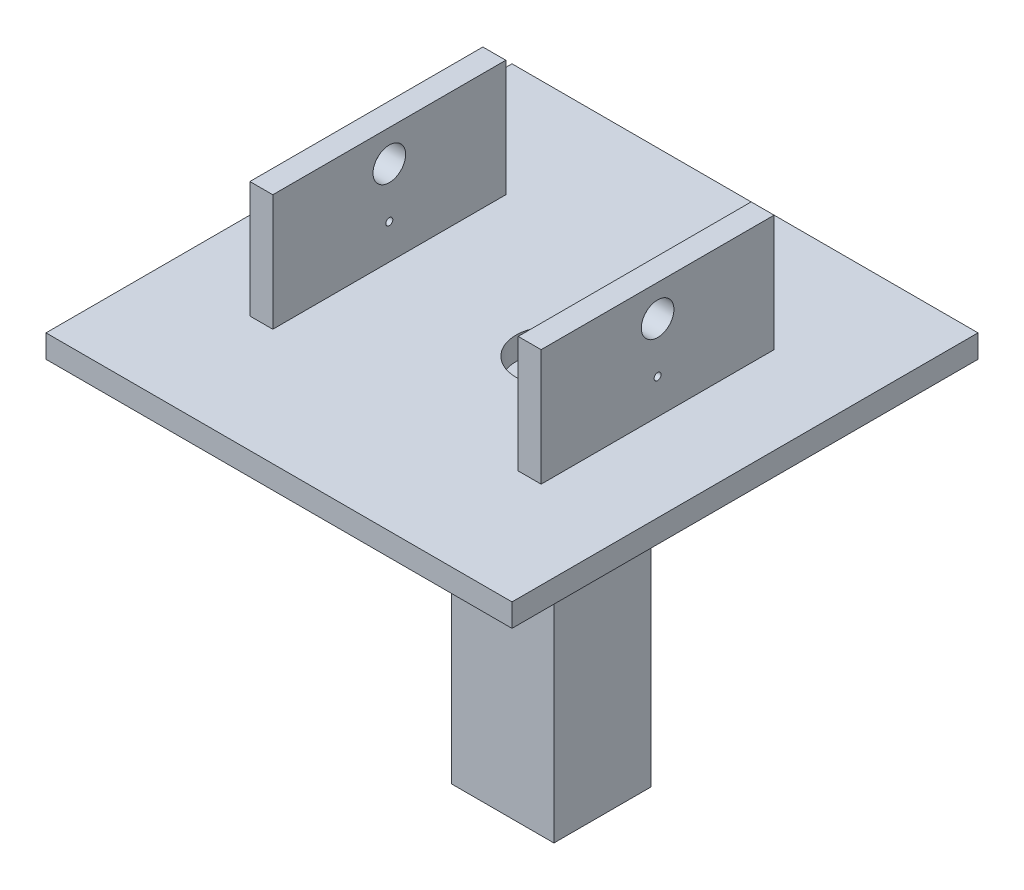
SolidWorks part; units mm, degrees
ref_plane "Front Plane" through (0, 0, 0) normal (0, 0, 1) x (1, 0, 0)
ref_plane "Top Plane" through (0, 0, 0) normal (0, 1, 0) x (1, 0, 0)
ref_plane "Right Plane" through (0, 0, 0) normal (1, 0, 0) x (0, 0, -1)
sketch "Sketch2" plane through (0, 0, 0) normal (0, 1, 0) x (1, 0, 0)
  line L1 (0, 0) -> (101.6, 0)
  line L2 (0, 0) -> (0, -101.6)
  line L3 (0, -101.6) -> (101.6, -101.6)
  line L4 (101.6, 0) -> (101.6, -101.6)
  dimension "D1" = 101.6
  dimension "D2" = 101.6
extrude "Boss-Extrude2" add sketch "Sketch2" along normal blind 5
sketch "Sketch3" plane through (0, 5, 0) normal (0, 1, 0) x (1, 0, 0)
  line L0 (0, 0) -> (0, -101.6) construction
  line L1 (19.05, -25.4) -> (24.05, -25.4)
  line L2 (19.05, -25.4) -> (19.05, -76.2)
  line L3 (19.05, -76.2) -> (24.05, -76.2)
  line L4 (24.05, -25.4) -> (24.05, -76.2)
  line L5 (0, -101.6) -> (101.6, -101.6) construction
  dimension "D1" = 5
  dimension "D2" = 19.05
  dimension "D3" = 50.8
  dimension "D4" = 25.4
extrude "Boss-Extrude3" add sketch "Sketch3" along normal blind 25.4
sketch "Sketch4" plane through (0, 5, 0) normal (0, 1, 0) x (1, 0, 0)
  line L0 (101.6, -101.6) -> (101.6, 0) construction
  line L1 (77.55, -25.4) -> (82.55, -25.4)
  line L2 (77.55, -25.4) -> (77.55, -76.2)
  line L3 (77.55, -76.2) -> (82.55, -76.2)
  line L4 (82.55, -25.4) -> (82.55, -76.2)
  line L5 (0, -101.6) -> (101.6, -101.6) construction
  dimension "D1" = 5
  dimension "D2" = 19.05
  dimension "D3" = 50.8
  dimension "D4" = 25.4
extrude "Boss-Extrude4" add sketch "Sketch4" along normal blind 25.4
sketch "Sketch8" plane through (19.05, 0, 0) normal (-1, 0, 0) x (0, 0, 1)
  line L0 (76.2, 30.4) -> (76.2, 5) construction
  line L1 (25.4, 5) -> (76.2, 5) construction
  circle A0 centre (50.8, 23.542) radius 3.556
  dimension "D1" = 25.4
  dimension "D2" = 18.542
extrude "Cut-Extrude1" cut sketch "Sketch8" against normal through all
sketch "Sketch9" plane through (82.55, 0, 0) normal (1, 0, 0) x (0, 0, -1)
  line L0 (-76.2, 30.4) -> (-76.2, 5) construction
  line L1 (-76.2, 5) -> (-25.4, 5) construction
  circle A0 centre (-50.8, 12.62) radius 0.762
  dimension "D1" = 25.4
  dimension "D2" = 7.62
extrude "Cut-Extrude2" cut sketch "Sketch9" against normal up to next
sketch "Sketch11" plane through (0, 5, 0) normal (0, 1, 0) x (1, 0, 0)
  line L0 (24.05, -76.2) -> (24.05, -25.4) construction
  line L1 (0, -101.6) -> (101.6, -101.6) construction
  circle A0 centre (59.61, -50.8) radius 7.9502
  dimension "D1" = 35.56
  dimension "D2" = 50.8
extrude "Cut-Extrude3" cut sketch "Sketch11" against normal through all
sketch "Sketch18" plane through (19.05, 0, 0) normal (-1, 0, 0) x (0, 0, 1)
  line L0 (0, 5) -> (101.6, 5) construction
  line L1 (25.4, 30.4) -> (25.4, 5) construction
  circle A0 centre (50.8, 12.62) radius 0.762
  dimension "D1" = 7.62
  dimension "D2" = 25.4
extrude "Cut-Extrude5" cut sketch "Sketch18" against normal up to next
sketch "Sketch19" plane through (0, 0, 0) normal (0, -1, 0) x (1, 0, 0)
  line L1 (48.1494, 61.3607) -> (70.4999, 61.3607)
  line L2 (48.1494, 61.3607) -> (48.1494, 40.1623)
  line L3 (48.1494, 40.1623) -> (70.4999, 40.1623)
  line L4 (70.4999, 61.3607) -> (70.4999, 40.1623)
extrude "Boss-Extrude5" add sketch "Sketch19" along normal blind 76.2
sketch "Sketch22" plane through (0, -76.2, 0) normal (0, -1, 0) x (1, 0, 0)
  circle A0 centre (59.61, 50.8) radius 5
extrude "Cut-Extrude6" cut sketch "Sketch22" against normal through all
